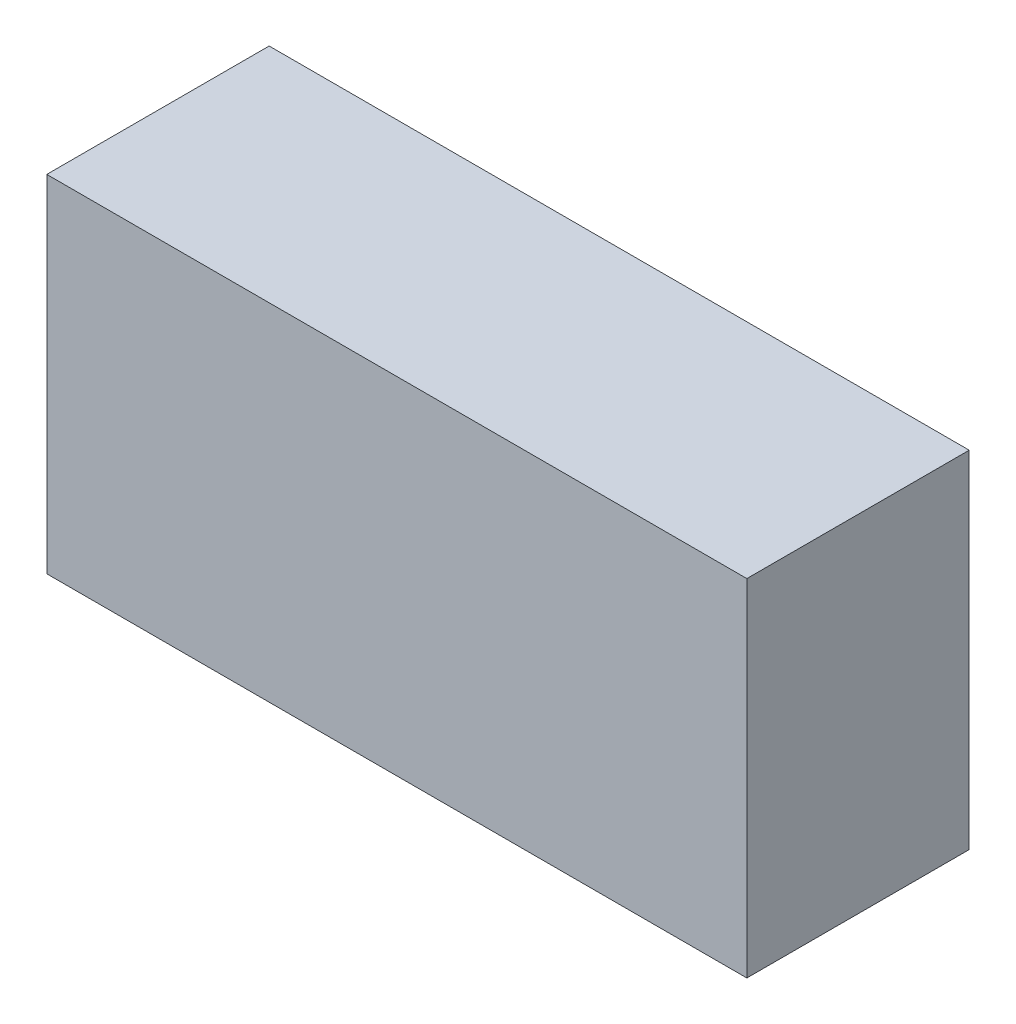
SolidWorks part; units mm, degrees
ref_plane "Front Plane" through (0, 0, 0) normal (0, 0, 1) x (1, 0, 0)
ref_plane "Top Plane" through (0, 0, 0) normal (0, 1, 0) x (1, 0, 0)
ref_plane "Right Plane" through (0, 0, 0) normal (1, 0, 0) x (0, 0, -1)
sketch "Sketch1" plane through (0, 0, 0) normal (0, 0, 1) x (1, 0, 0)
  line L1 (0, 0) -> (85, 0)
  line L2 (0, 0) -> (0, -42)
  line L3 (0, -42) -> (85, -42)
  line L4 (85, 0) -> (85, -42)
  dimension "D1" = 85
  dimension "D2" = 42
extrude "Boss-Extrude1" add sketch "Sketch1" along normal blind 27
